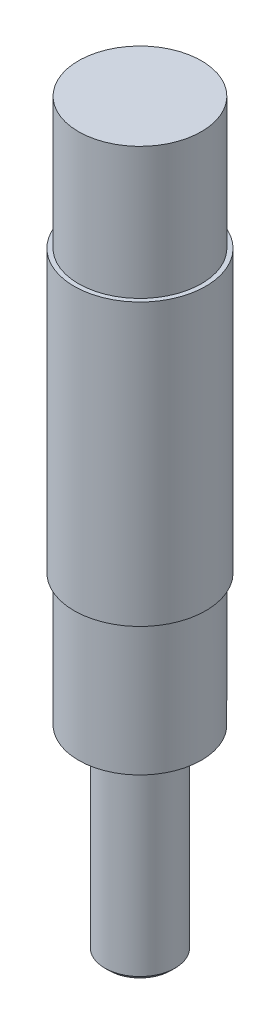
SolidWorks part; units mm, degrees
ref_plane "Front Plane" through (0, 0, 0) normal (0, 0, 1) x (1, 0, 0)
ref_plane "Top Plane" through (0, 0, 0) normal (0, 1, 0) x (1, 0, 0)
ref_plane "Right Plane" through (0, 0, 0) normal (1, 0, 0) x (0, 0, -1)
sketch "Sketch1" plane through (0, 0, 0) normal (0, 1, 0) x (1, 0, 0)
  circle A0 centre (0, 0) radius 7.5
  dimension "D1" = 15
extrude "Boss-Extrude1" add sketch "Sketch1" along normal blind 32
sketch "Sketch2" plane through (0, 32, 0) normal (0, 1, 0) x (1, 0, 0)
  circle A0 centre (0, 0) radius 7
  dimension "D1" = 14
extrude "Boss-Extrude2" add sketch "Sketch2" along normal blind 15
cosmetic thread "Cosmetic Thread1"
sketch "Sketch3" plane through (0, 0, 0) normal (0, -1, 0) x (1, 0, 0)
  circle A0 centre (0, 0) radius 7
  dimension "D1" = 14
extrude "Boss-Extrude3" add sketch "Sketch3" along normal blind 15
cosmetic thread "Cosmetic Thread2" parameters "D2"=11.797
sketch "Sketch4" plane through (0, -15, 0) normal (0, -1, 0) x (1, 0, 0)
  circle A0 centre (0, 0) radius 4
  dimension "D1" = 8
extrude "Boss-Extrude4" add sketch "Sketch4" along normal blind 22.5
chamfer "Chamfer1" distance 0.5 angle 45 1 edges at (0, -37.5, -4)
